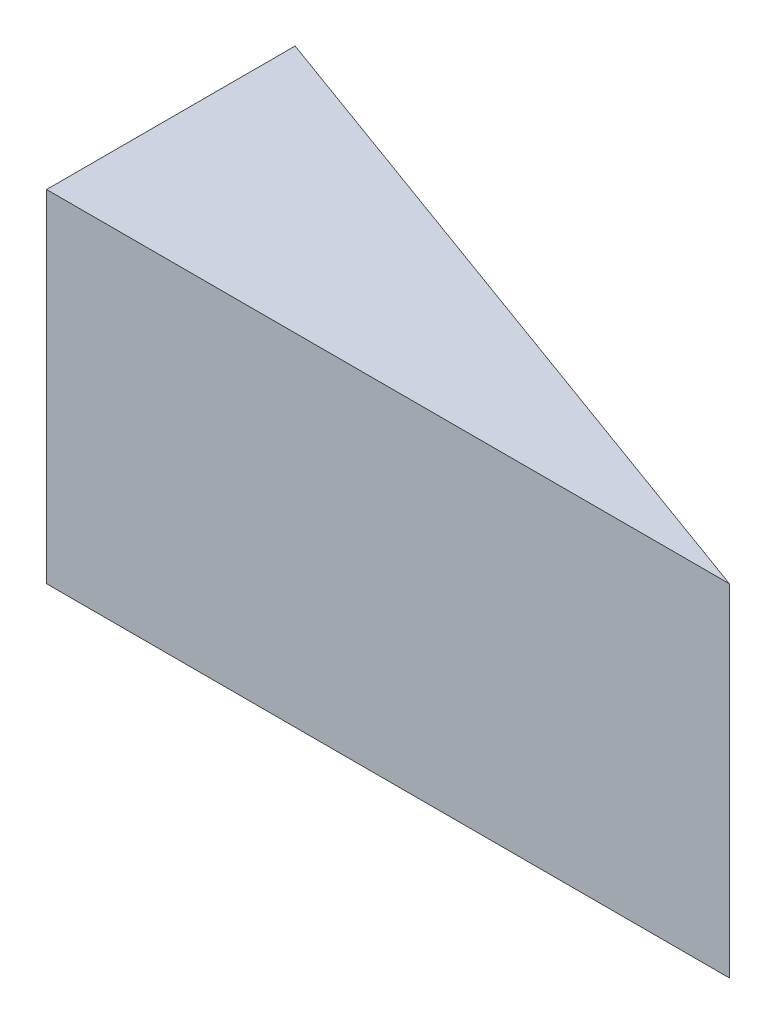
SolidWorks part; units mm, degrees
ref_plane "Přední rovina" through (0, 0, 0) normal (0, 0, 1) x (1, 0, 0)
ref_plane "Horní rovina" through (0, 0, 0) normal (0, 1, 0) x (1, 0, 0)
ref_plane "Pravá rovina" through (0, 0, 0) normal (1, 0, 0) x (0, 0, -1)
sketch "Sketch1" plane through (0, 0, 0) normal (0, 1, 0) x (1, 0, 0)
  line L0 (0, 0) -> (40, 0)
  line L1 (40, 0) -> (0, 14.5588)
  line L2 (0, 14.5588) -> (0, 0)
  point P4 (0, 0)
  point P5 (0, 0)
  point P6 (0, 16.8591)
  dimension "D1" = 20
  dimension "D2" = 40
extrude "Boss-Extrude1" add sketch "Sketch1" along normal blind 20
